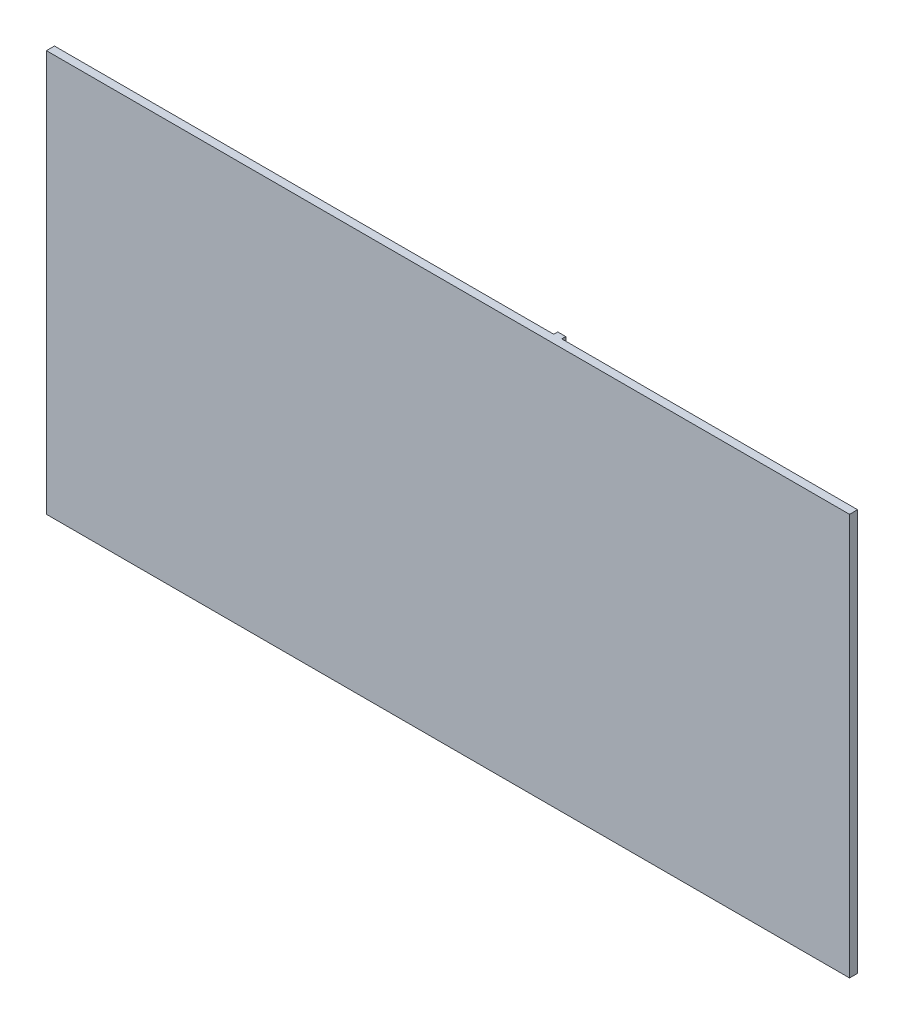
SolidWorks part; units mm, degrees
ref_plane "前视基准面" through (0, 0, 0) normal (0, 0, 1) x (1, 0, 0)
ref_plane "上视基准面" through (0, 0, 0) normal (0, 1, 0) x (1, 0, 0)
ref_plane "右视基准面" through (0, 0, 0) normal (1, 0, 0) x (0, 0, -1)
other "Configuration Table"
sketch "草图1" plane through (0, 0, 0) normal (0, 0, 1) x (1, 0, 0)
  line L1 (-500, 250) -> (500, 250)
  line L2 (-500, 250) -> (-500, -250)
  line L3 (-500, -250) -> (500, -250)
  line L4 (500, 250) -> (500, -250)
  line L5 (-500, 250) -> (500, -250) construction
  line L6 (-500, -250) -> (500, 250) construction
  point P0 (0, 0)
  dimension "D1" = 1000
  dimension "D2" = 500
extrude "凸台-拉伸1" add sketch "草图1" along normal blind 10
sketch "草图2" plane through (0, 0, 0) normal (0, 0, -1) x (-1, 0, 0)
  line L0 (-500, 250) -> (500, 250) construction
  line L1 (-131.636, 250) -> (-121.636, 250)
  line L2 (-131.636, 250) -> (-131.636, -250)
  line L3 (-131.636, -250) -> (-121.636, -250)
  line L4 (-121.636, 250) -> (-121.636, -250)
  line L5 (500, -250) -> (-500, -250) construction
  dimension "D1" = 10
extrude "凸台-拉伸2" add sketch "草图2" along normal blind 5
